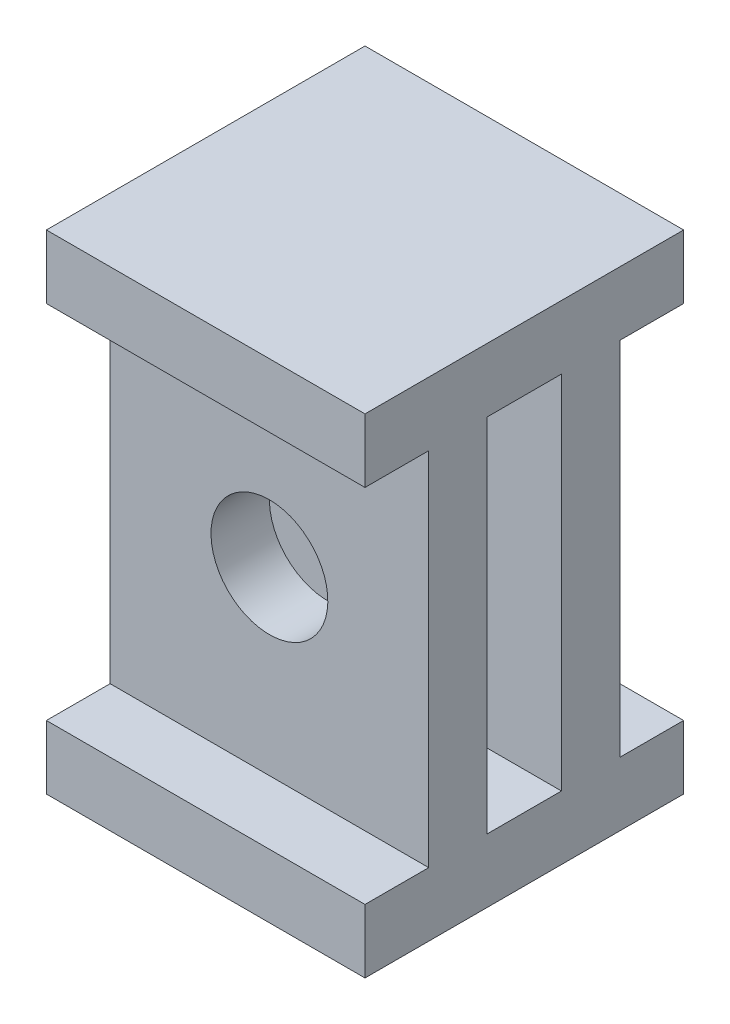
SolidWorks part; units mm, degrees
ref_plane "Front Plane" through (0, 0, 0) normal (0, 0, 1) x (1, 0, 0)
ref_plane "Top Plane" through (0, 0, 0) normal (0, 1, 0) x (1, 0, 0)
ref_plane "Right Plane" through (0, 0, 0) normal (1, 0, 0) x (0, 0, -1)
sketch "Sketch1" plane through (0, 0, 0) normal (0, 1, 0) x (1, 0, 0)
  line L1 (0, 0) -> (15, 0)
  line L2 (0, 0) -> (0, 7.5)
  line L3 (0, 7.5) -> (15, 7.5)
  line L4 (15, 0) -> (15, 7.5)
  dimension "D1" = 7.5
  dimension "D2" = 15
extrude "Boss-Extrude1" add sketch "Sketch1" along normal blind 23
mirror "Mirror1" about plane through (0, 23, 0) normal (0, 0, -1) of bodies 101 106
sketch "Sketch10" plane through (15, 0, 0) normal (1, 0, 0) x (0, 0, -1)
  line L0 (-7.5, 23) -> (-7.5, 0) construction
  line L1 (-7.5, 20) -> (-4.5, 20)
  line L2 (-7.5, 20) -> (-7.5, 3)
  line L3 (-7.5, 3) -> (-4.5, 3)
  line L4 (-4.5, 20) -> (-4.5, 3)
  line L5 (7.5, 23) -> (7.5, 0) construction
  line L6 (7.5, 20) -> (4.5, 20)
  line L7 (7.5, 20) -> (7.5, 3)
  line L8 (7.5, 3) -> (4.5, 3)
  line L9 (4.5, 20) -> (4.5, 3)
  line L10 (7.5, 23) -> (-7.5, 23) construction
  line L11 (-1.75, 20) -> (1.75, 20)
  line L12 (-1.75, 20) -> (-1.75, 3)
  line L13 (-1.75, 3) -> (1.75, 3)
  line L14 (1.75, 20) -> (1.75, 3)
  line L15 (7.5, 0) -> (-7.5, 0) construction
  line L16 (0, 23) -> (0, 0) construction
  line L18 (-7.5, 23) -> (7.5, 23) construction
  dimension "D1" = 3
  dimension "D2" = 3
  dimension "D3" = 1.75
  dimension "D4" = 4.5
  dimension "D5" = 1.75
  dimension "D6" = 4.5
extrude "Cut-Extrude5" cut sketch "Sketch10" against normal through all
sketch "Sketch11" plane through (0, 0, -4.5) normal (0, 0, -1) x (-1, 0, 0)
  line L0 (-7.5, 20) -> (-7.5, 3) construction
  line L1 (0, 20) -> (-15, 20) construction
  line L2 (0, 3) -> (-15, 3) construction
  circle A0 centre (-7.5, 11.5) radius 2.75
  dimension "D1" = 5.5
extrude "Cut-Extrude6" cut sketch "Sketch11" against normal through all
